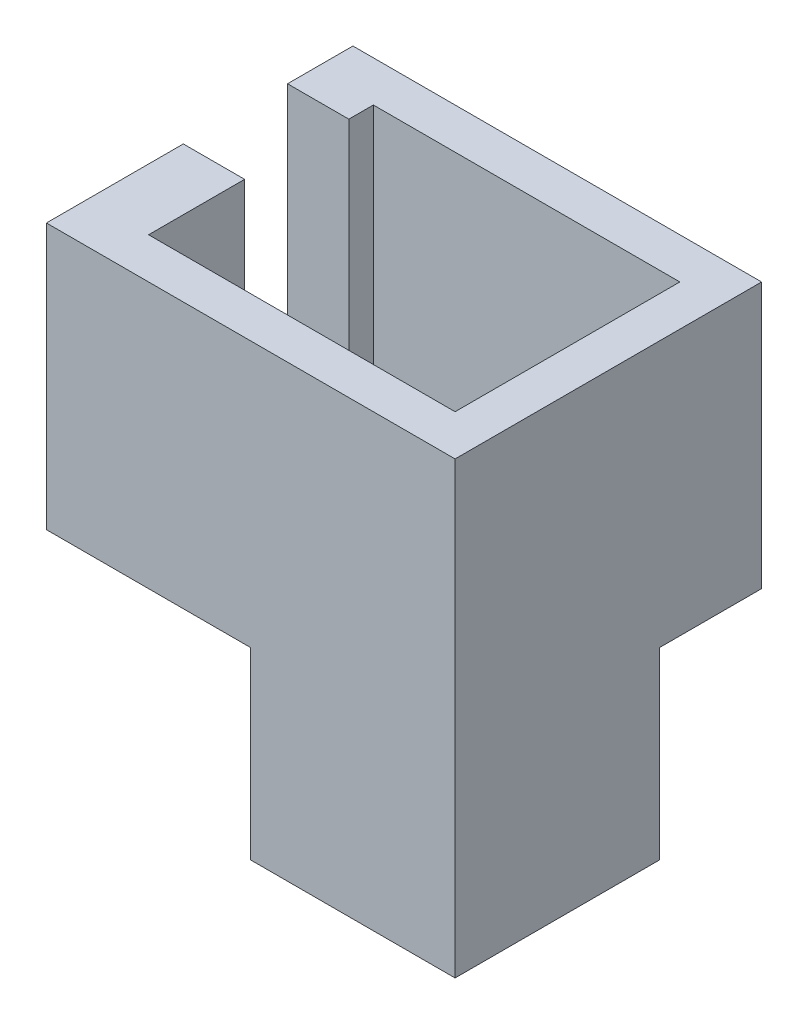
SolidWorks part; units mm, degrees
ref_plane "Front Plane" through (0, 0, 0) normal (0, 0, 1) x (1, 0, 0)
ref_plane "Top Plane" through (0, 0, 0) normal (0, 1, 0) x (1, 0, 0)
ref_plane "Right Plane" through (0, 0, 0) normal (1, 0, 0) x (0, 0, -1)
sketch "Sketch1" plane through (0, 0, 0) normal (0, 1, 0) x (1, 0, 0)
  line L3 (3, 2) -> (18, 2)
  line L8 (18, 2) -> (18, 13)
  line L11 (18, 13) -> (3, 13)
  line L13 (20, 0) -> (20, 15)
  line L15 (0, 15) -> (20, 15)
  line L22 (0, 6.7) -> (3, 6.7)
  line L23 (3, 2) -> (3, 6.7)
  line L24 (0, 0) -> (20, 0)
  line L25 (0, 0) -> (0, 6.7)
  line L29 (0, 15) -> (0, 11.8)
  line L30 (0, 11.8) -> (3, 11.8)
  line L31 (3, 11.8) -> (3, 13)
  dimension "D1" = 2
  dimension "D2" = 15
  dimension "D3" = 20
  dimension "D4" = 2
  dimension "D5" = 20
  dimension "D6" = 2
  dimension "D7" = 3.2
  dimension "D8" = 6.7
  dimension "D9" = 3
  dimension "D10" = 3
extrude "Boss-Extrude1" add sketch "Sketch1" along normal blind 12
sketch "Sketch3" plane through (0, 0, 0) normal (0, -1, 0) x (1, 0, 0)
  line L1 (20, 0) -> (0, 0)
  line L2 (20, 0) -> (20, -15)
  line L3 (20, -15) -> (0, -15)
  line L4 (0, 0) -> (0, -15)
extrude "Boss-Extrude2" add sketch "Sketch3" along normal blind 1
sketch "Sketch4" plane through (0, -1, 0) normal (0, -1, 0) x (1, 0, 0)
  line L1 (20, 0) -> (10, 0)
  line L2 (20, 0) -> (20, -10)
  line L3 (20, -10) -> (10, -10)
  line L4 (10, 0) -> (10, -10)
  line L5 (20, 0) -> (0, 0) construction
  dimension "D1" = 10
  dimension "D2" = 10
  dimension "D3" = 0
extrude "Boss-Extrude3" add sketch "Sketch4" along normal blind 9
